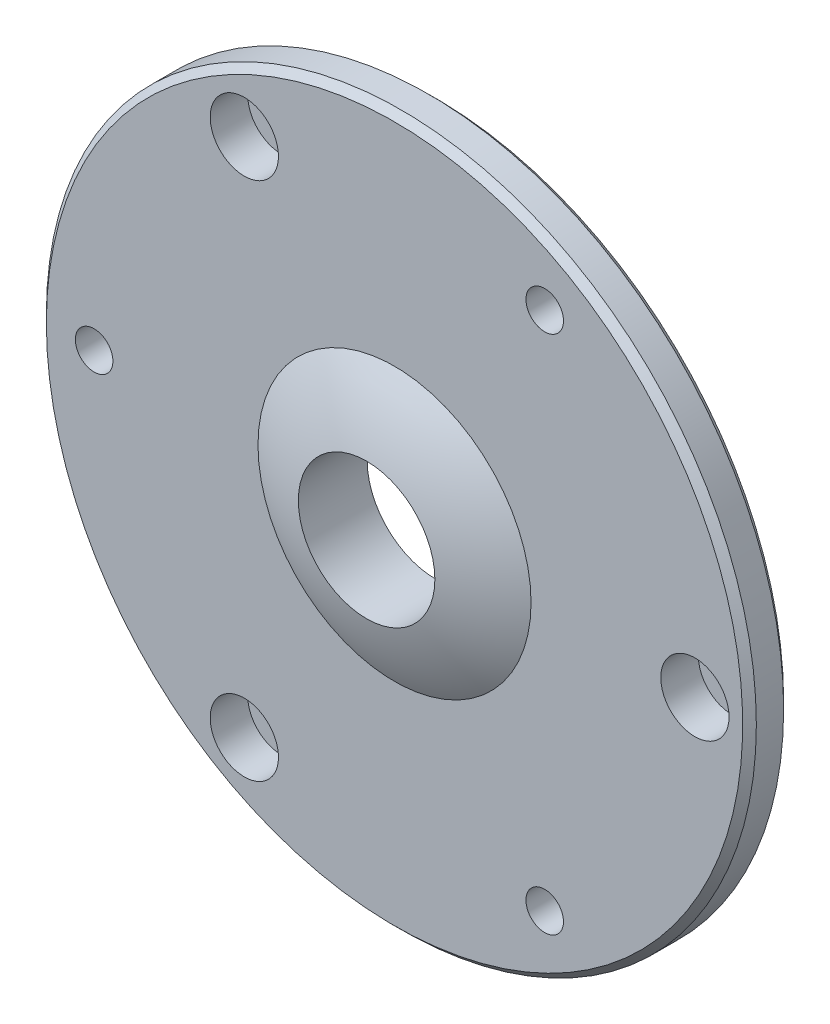
SolidWorks part; units mm, degrees
ref_plane "前视基准面" through (0, 0, 0) normal (0, 0, 1) x (1, 0, 0)
ref_plane "上视基准面" through (0, 0, 0) normal (0, 1, 0) x (1, 0, 0)
ref_plane "右视基准面" through (0, 0, 0) normal (1, 0, 0) x (0, 0, -1)
other "Configuration Table"
sketch "Sk_cover" plane through (0, 0, 0) normal (0, 1, 0) x (1, 0, 0)
  line L0 (10, 0) -> (52, 0)
  line L1 (52, 0) -> (52, -6)
  line L2 (52, -6) -> (20, -6)
  line L3 (10, -10.0888) -> (10, 0)
  line L4 (0, 0) -> (0, -12) construction
  arc A0 (20, -6) -> (10, -10.0888) centre (0, 28.641) cw
revolve "Rev_cover" add sketch "Sk_cover" angle 360 about L4
sketch "Sk_h0" plane through (0, 0, 0) normal (0, 0, 1) x (1, 0, 0)
  circle A0 centre (44, 0) radius 2.75
extrude "Cut_h0" cut sketch "Sk_h0" along normal through all
sketch "Sk_h1" plane through (0, 0, 0) normal (0, 0, 1) x (1, 0, 0)
  circle A0 centre (-22, 38.1051) radius 2.75
extrude "Cut_h1" cut sketch "Sk_h1" along normal through all
sketch "Sk_h2" plane through (0, 0, 0) normal (0, 0, 1) x (1, 0, 0)
  circle A0 centre (-22, -38.1051) radius 2.75
extrude "Cut_h2" cut sketch "Sk_h2" along normal through all
sketch "Sk_h60" plane through (0, 0, 0) normal (0, 0, 1) x (1, 0, 0)
  circle A0 centre (22, 38.1051) radius 2.75
extrude "Cut_h60" cut sketch "Sk_h60" along normal through all
sketch "Sk_h180" plane through (0, 0, 0) normal (0, 0, 1) x (1, 0, 0)
  circle A0 centre (-44, 0) radius 2.75
extrude "Cut_h180" cut sketch "Sk_h180" along normal through all
sketch "Sk_h300" plane through (0, 0, 0) normal (0, 0, 1) x (1, 0, 0)
  circle A0 centre (22, -38.1051) radius 2.75
extrude "Cut_h300" cut sketch "Sk_h300" along normal through all
ref_plane "P_cb" through (0, 0, 3.75) normal (0, 0, 1) x (1, 0, 0)
sketch "Sk_cb0" plane through (0, 0, 3.75) normal (0, 0, 1) x (1, 0, 0)
  circle A0 centre (44, 0) radius 5
extrude "Cut_cb0" cut sketch "Sk_cb0" against normal mid plane 6.5
sketch "Sk_cb1" plane through (0, 0, 3.75) normal (0, 0, 1) x (1, 0, 0)
  circle A0 centre (-22, 38.1051) radius 5
extrude "Cut_cb1" cut sketch "Sk_cb1" against normal mid plane 6.5
sketch "Sk_cb2" plane through (0, 0, 3.75) normal (0, 0, 1) x (1, 0, 0)
  circle A0 centre (-22, -38.1051) radius 5
extrude "Cut_cb2" cut sketch "Sk_cb2" against normal mid plane 6.5
sketch "Sk_groove70" plane through (0, 0, 0) normal (0, 0, 1) x (1, 0, 0)
  circle A0 centre (0, 0) radius 33.1
  circle A1 centre (0, 0) radius 36.9
extrude "Cut_groove70" cut sketch "Sk_groove70" along normal blind 2.4
chamfer "Chamfer_C1" distance 1 angle 45 2 edges at (-52, 0, 6) (-52, 0, 0)
